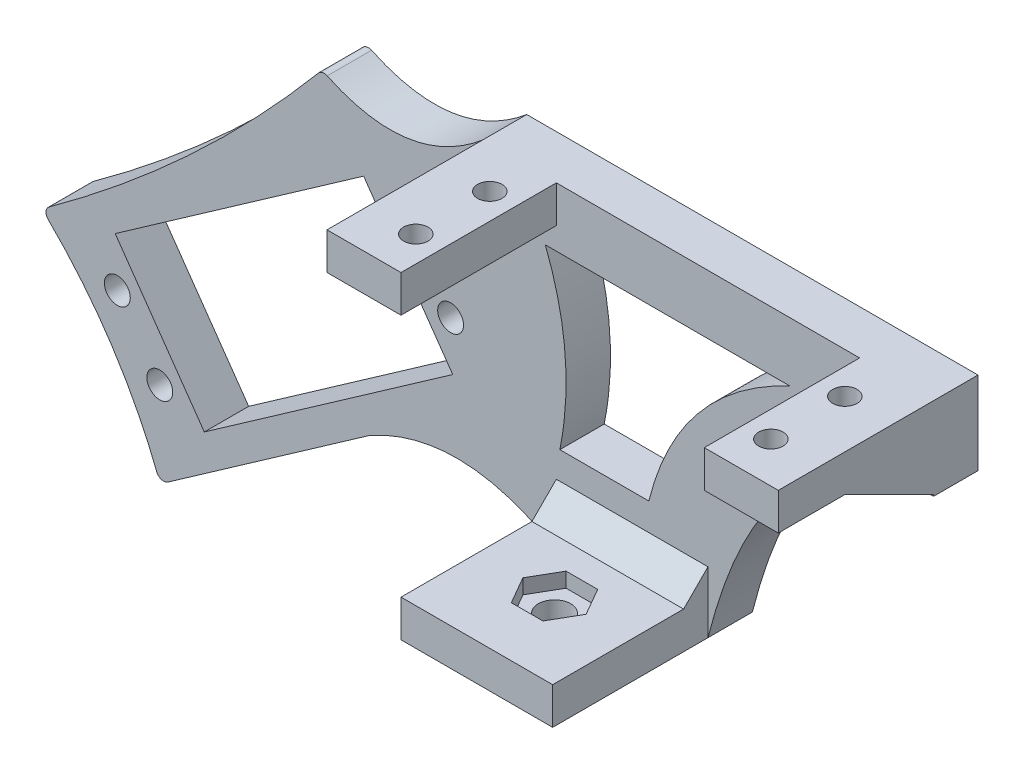
SolidWorks part; units mm, degrees
ref_plane "Front Plane" through (0, 0, 0) normal (0, 0, 1) x (1, 0, 0)
ref_plane "Top Plane" through (0, 0, 0) normal (0, 1, 0) x (1, 0, 0)
ref_plane "Right Plane" through (0, 0, 0) normal (1, 0, 0) x (0, 0, -1)
sketch "Sketch1" plane through (0, 0, 0) normal (0, 0, 1) x (1, 0, 0)
  line L5 (-36.2967, 22.2901) -> (-26.2967, 22.2901)
  line L6 (-36.2967, 22.2901) -> (-36.2967, 17.2901)
  line L7 (-36.2967, 17.2901) -> (-26.2967, 17.2901)
  line L8 (-26.2967, 22.2901) -> (-26.2967, 17.2901)
  line L9 (-36.2967, 22.2901) -> (-26.2967, 17.2901) construction
  line L10 (-36.2967, 17.2901) -> (-26.2967, 22.2901) construction
  line L11 (14.7033, 22.2901) -> (24.7033, 22.2901)
  line L12 (14.7033, 22.2901) -> (14.7033, 17.2901)
  line L13 (14.7033, 17.2901) -> (24.7033, 17.2901)
  line L14 (24.7033, 22.2901) -> (24.7033, 17.2901)
  line L15 (14.7033, 22.2901) -> (24.7033, 17.2901) construction
  line L16 (14.7033, 17.2901) -> (24.7033, 22.2901) construction
  point P0 (-31.2967, 19.7901)
  point P6 (19.7033, 19.7901)
  dimension "D1" = 5
  dimension "D2" = 5
  dimension "D3" = 10
  dimension "D4" = 10
  dimension "D5" = 41
extrude "Boss-Extrude1" add sketch "Sketch1" along normal blind 21
sketch "Sketch2" plane through (0, 0, 21) normal (0, 0, 1) x (1, 0, 0)
  line L0 (-36.2967, 22.2901) -> (24.7033, 22.2901)
  line L1 (24.7033, 22.2901) -> (24.7033, 7.2901)
  line L2 (24.7033, 7.2901) -> (12.7033, 7.2901)
  line L3 (12.7033, 7.2901) -> (-5.7967, -11.2099)
  line L4 (-5.7967, -11.2099) -> (-5.7967, -20.7099)
  line L5 (-5.7967, -20.7099) -> (-36.2967, -20.7099)
  line L6 (-36.2967, -20.7099) -> (-36.2967, 22.2901)
  line L7 (-36.2967, 17.2901) -> (-26.2967, 17.2901) construction
  line L8 (-16.0467, 22.2901) -> (-16.0467, 2.0298) construction
  line L9 (-26.2967, 17.2901) -> (-26.2967, 22.2901) construction
  line L10 (3.5612, 12.2901) -> (-15.7967, -7.0678)
  line L11 (-15.7967, -7.0678) -> (-15.7967, -10.7099)
  line L12 (-15.7967, -10.7099) -> (-26.2967, -10.7099)
  line L13 (-26.2967, -10.7099) -> (-26.2967, 12.2901)
  line L14 (-26.2967, 12.2901) -> (3.5612, 12.2901)
  line L15 (3.5612, 12.2901) -> (3.5612, 12.2901)
  line L16 (3.5612, 12.2901) -> (3.5612, 12.2901)
  dimension "D1" = 38
  dimension "D2" = 15
  dimension "D3" = 10.25
  dimension "D4" = 10.25
  dimension "D5" = 135
  dimension "D6" = 12
  dimension "D7" = 10
extrude "Boss-Extrude2" add sketch "Sketch2" along normal blind 6 contours L6 L0 L1 L2 L3 L4 L5
sketch "Sketch3" plane through (0, 0, 21) normal (0, 0, -1) x (-1, 0, 0)
  line L1 (5.7967, -20.7099) -> (26.2967, -20.7099)
  line L2 (5.7967, -20.7099) -> (5.7967, -15.7099)
  line L3 (5.7967, -15.7099) -> (26.2967, -15.7099)
  line L4 (26.2967, -20.7099) -> (26.2967, -15.7099)
  line L5 (16.0467, 22.2901) -> (16.0467, 17.3696) construction
  line L6 (-14.7033, 22.2901) -> (26.2967, 22.2901) construction
  line L7 (26.2967, 17.2901) -> (26.2967, 22.2901) construction
  line L9 (26.2967, 17.2901) -> (26.2967, 22.2901) construction
  dimension "D1" = 5
  dimension "D2" = 10.25
extrude "Boss-Extrude3" add sketch "Sketch3" along normal blind 21
sketch "Sketch4" plane through (0, 22.2901, 0) normal (0, 1, 0) x (1, 0, 0)
  line L0 (-26.2967, 0) -> (-26.2967, -21) construction
  line L1 (-26.2967, -10.5) -> (-23.5726, -10.5) construction
  line L2 (-26.2967, -21) -> (-26.2967, 0) construction
  circle A0 centre (-29.7967, -5.5) radius 1.65
  circle A1 centre (18.2033, -5.5) radius 1.65
  circle A2 centre (18.2033, -15.5) radius 1.65
  circle A3 centre (-29.7967, -15.5) radius 1.65
  dimension "D1" = 3.3
  dimension "D2" = 3.5
  dimension "D3" = 5
  dimension "D4" = 2
  dimension "D5" = 2
extrude "Cut-Extrude1" cut sketch "Sketch4" against normal up to next
sketch "Sketch5" plane through (0, -15.7099, 0) normal (0, 1, 0) x (1, 0, 0)
  line L0 (-26.2967, 0) -> (-5.7967, 0) construction
  line L1 (-5.7967, 0) -> (-5.7967, -21) construction
  circle A0 centre (-16.0467, -10.5) radius 2.2
  dimension "D1" = 4.4
  dimension "D3" = 10.25
  dimension "D2" = 10.5
extrude "Cut-Extrude2" cut sketch "Sketch5" against normal up to next
sketch "Sketch6" plane through (0, 0, 27) normal (0, 0, 1) x (1, 0, 0)
  line L0 (-36.2967, 22.2901) -> (-36.2967, -20.7099) construction
  line L1 (-85.9329, -13.4688) -> (-52.3477, 10.0479)
  line L2 (-85.9329, -13.4688) -> (-73.8878, -30.671)
  line L3 (-73.8878, -30.671) -> (-40.3026, -7.1543)
  line L4 (-52.3477, 10.0479) -> (-40.3026, -7.1543)
  line L5 (-85.9329, -13.4688) -> (-40.3026, -7.1543) construction
  line L6 (-73.8878, -30.671) -> (-52.3477, 10.0479) construction
  line L7 (-79.8591, -39.7352) -> (-51.5037, -19.8806)
  line L8 (-71.9651, -45.841) -> (-23.4502, -45.841) construction
  line L9 (-79.9104, -22.0699) -> (-76.182, -19.4593) construction
  line L10 (-36.2967, 22.2901) -> (-36.2967, -20.7099)
  line L11 (-36.2967, -20.7099) -> (-5.7967, -20.7099) construction
  circle A0 centre (-85.6453, -19.9816) radius 1.75
  circle A1 centre (-79.9095, -28.1732) radius 1.75
  circle A2 centre (-46.326, 7.55) radius 1.75
  circle A3 centre (-40.5902, -0.6415) radius 1.75
  spline S0 degree 2 poles (-95.8421, -15.5242) (-74.6637, -0.3481) (-57.9628, 19.6612) knots 0 0 0 1 1 1
  spline S1 degree 2 poles (-57.9628, 19.6612) (-46.4471, 13.8149) (-36.2967, 22.2901) knots 0 0 0 1 1 1
  spline S2 degree 2 poles (-95.8421, -15.5242) (-85.0867, -25.7546) (-79.8591, -39.7352) knots 0 0 0 1 1 1
  spline S3 degree 2 poles (-51.5037, -19.8806) (-43.7779, -18.4911) (-36.2967, -20.7099) knots 0 0 0 1 1 1
  point P0 (-63.1177, -10.3116)
  line M9 (-36.2967, 22.2901) -> (-36.2967, -20.7099)
  dimension "D5" = 3.5
  dimension "D8" = 3.5
  dimension "D9" = 3.5
  dimension "D10" = 3.5
  dimension "D1" = 41
  dimension "D2" = 21
  dimension "D3" = 8
  dimension "D4" = 35
  dimension "D6" = 3.5
  dimension "D7" = 5
  dimension "D11" = 3.5
  dimension "D12" = 10
  dimension "D13" = 10
  dimension "D14" = 3.5
  dimension "D15" = 3.5
  dimension "D16" = 5
  dimension "D17" = 4
  dimension "D18" = 4
extrude "Boss-Extrude4" add sketch "Sketch6" against normal up to surface (6 mm away) contours L7 S3 A3 S1 S0 S2 L1 L4 L3 L2 A0 A1 A2 M9 up to face at (-7.5275, 3.4055, 21)
sketch "Sketch7" plane through (0, 0, 21) normal (0, 0, -1) x (-1, 0, 0)
  line L0 (36.2967, -20.7099) -> (26.2967, -20.7099) construction
  line L1 (36.2967, -20.7099) -> (26.2967, -20.7099)
  parabola Q0 (51.5037, -19.8806) -> (36.2967, -20.7099) focus (44.501, -35.4126) apex (43.4171, -19.419) construction
  parabola Q1 (51.5037, -19.8806) -> (36.2967, -20.7099) focus (44.501, -35.4126) apex (43.4171, -19.419)
  spline S0 degree 2 poles (26.2967, -20.7099) (39.1597, -13.0568) (51.5037, -19.8806) knots 0 0 0 1 1 1
extrude "Cut-Extrude3" cut sketch "Sketch7" against normal up to next
sketch "Sketch10" plane through (0, 0, 27) normal (0, 0, 1) x (1, 0, 0)
  line L0 (5.2668, 14.2901) -> (-27.7882, 14.2901)
  line L1 (-36.2967, 22.2901) -> (24.7033, 22.2901) construction
  line L2 (-25.8237, -8.7099) -> (-13.7967, -8.7099)
  line L3 (-5.7967, -11.2099) -> (-5.7967, -20.7099) construction
  line L4 (-5.7967, -20.7099) -> (-26.2967, -20.7099) construction
  spline S2 degree 2 poles (5.2668, 14.2901) (-9.8422, 7.1853) (-13.7967, -8.7099) knots 0 0 0 1 1 1
  spline S3 degree 2 poles (-27.7882, 14.2901) (-23.4314, 3.1329) (-25.8237, -8.7099) knots 0 0 0 1 1 1
  dimension "D1" = 8
  dimension "D2" = 8
  dimension "D3" = 12
extrude "Cut-Extrude7" cut sketch "Sketch10" against normal up to next
sketch "Sketch11" plane through (0, 0, 27) normal (0, 0, 1) x (1, 0, 0)
  line L1 (24.7033, 7.2901) -> (12.7033, 7.2901) construction
  line L2 (12.7033, 7.2901) -> (-5.7967, -11.2099) construction
  line L3 (-5.7967, -11.2099) -> (-5.7967, -20.7099) construction
  line L4 (15.1192, 7.2901) -> (12.7033, 7.2901)
  line L5 (12.7033, 7.2901) -> (-5.7967, -11.2099)
  line L6 (-5.7967, -11.2099) -> (-5.7967, -20.7099)
  spline S0 degree 2 poles (-5.7967, -20.7099) (-0.0669, -3.0227) (15.1192, 7.2901) knots 0 0 0 1 1 1
extrude "Boss-Extrude5" add sketch "Sketch11" against normal up to surface (6 mm away) up to face at (-18.1639, 2.7901, 21)
sketch "Sketch12" plane through (24.7033, 0, 0) normal (1, 0, 0) x (0, 0, -1)
  line L0 (-21, 11.2901) -> (-9, 17.2901)
  line L1 (-21, 17.2901) -> (-21, 7.2901) construction
  line L2 (-21, 17.2901) -> (0, 17.2901) construction
  line L3 (-9, 17.2901) -> (-21, 17.2901)
  line L4 (-21, 17.2901) -> (-21, 11.2901)
  dimension "D1" = 6
  dimension "D2" = 12
extrude "Boss-Extrude6" add sketch "Sketch12" against normal blind 3
sketch "Sketch13" plane through (-36.2967, 0, 0) normal (-1, 0, 0) x (0, 0, 1)
  line L3 (21, 11.2901) -> (21, 17.2901)
  line L4 (21, 17.2901) -> (9, 17.2901)
  line L5 (9, 17.2901) -> (21, 11.2901)
  line L6 (21, 11.2901) -> (21, 17.2901)
  line L7 (21, 17.2901) -> (9, 17.2901)
  line L8 (9, 17.2901) -> (21, 11.2901)
  dimension "D1" = 0
extrude "Boss-Extrude7" add sketch "Sketch13" against normal blind 3
sketch "Sketch14" plane through (-5.7967, 0, 0) normal (1, 0, 0) x (0, 0, -1)
  line L0 (-17.7, -15.7099) -> (-21, -12.4099)
  line L1 (0, -15.7099) -> (-21, -15.7099) construction
  line L2 (-21, -20.7099) -> (-21, 7.2901) construction
  line L3 (-21, -12.4099) -> (-21, -15.7099)
  line L4 (-21, -15.7099) -> (-17.7, -15.7099)
  dimension "D1" = 3.3
  dimension "D2" = 3.3
extrude "Boss-Extrude8" add sketch "Sketch14" against normal up to surface (20.5 mm away) up to face at (-26.2967, -18.2099, 10.5)
ref_plane "Plane1" through (0, 0, 24) normal (0, 0, -1) x (-1, 0, 0)
mirror "Mirror1" about plane through (0, 0, 24) normal (0, 0, -1) of "Cut-Extrude2", "Boss-Extrude1", "Cut-Extrude1", "Boss-Extrude6", "Boss-Extrude7", "Boss-Extrude8", "Boss-Extrude3"
sketch "Sketch16" plane through (0, 0, 0) normal (0, 0, -1) x (-1, 0, 0)
  line L1 (-24.7033, 22.2901) -> (36.7204, 22.2901)
  line L2 (-24.7033, 22.2901) -> (-24.7033, -23.0622)
  line L3 (-24.7033, -23.0622) -> (36.7204, -23.0622)
  line L4 (36.7204, 22.2901) -> (36.7204, -23.0622)
extrude "Cut-Extrude8" cut sketch "Sketch16" against normal up to surface (21 mm away) up to face at (-18.1639, 2.7901, 21)
sketch "Sketch17" plane through (0, 0, 21) normal (0, 0, -1) x (-1, 0, 0)
  line L0 (-24.7033, 7.2901) -> (-24.7033, 11.0901)
  line L1 (-24.7033, 22.2901) -> (-24.7033, 7.2901) construction
  line L2 (-24.7033, 7.2901) -> (-15.1192, 7.2901) construction
  line L3 (-24.7033, 7.2901) -> (-15.1192, 7.2901)
  parabola Q0 (5.7967, -20.7099) -> (-15.1192, 7.2901) focus (-23.0101, -19.6791) apex (-2.9383, -4.0263) construction
  parabola Q1 (5.7967, -20.7099) -> (-15.1192, 7.2901) focus (-23.0101, -19.6791) apex (-2.9383, -4.0263)
  spline S0 degree 2 poles (5.7967, -20.7099) (-1.8909, 9.8453) (-24.7033, 11.0901) knots 0 0 0 1 1 1
  dimension "D1" = 3.8
  dimension "D2" = 3.5
  dimension "D3" = 3
extrude "Cut-Extrude9" cut sketch "Sketch17" against normal up to surface (6 mm away) up to face at (-18.1639, 2.7901, 27)
fillet "Fillet1" radius 1 3 edges at (-79.8591, -39.7352, 24) (-95.8421, -15.5242, 24) (-57.9628, 19.6612, 24)
sketch "Sketch18" plane through (0, -15.7099, 0) normal (0, 1, 0) x (1, 0, 0)
  line L0 (-26.2967, -30.3) -> (-5.7967, -30.3) construction
  line L1 (-18.1829, -41.2) -> (-13.9105, -41.2)
  line L2 (-13.9105, -41.2) -> (-11.7743, -37.5)
  line L3 (-11.7743, -37.5) -> (-13.9105, -33.8)
  line L4 (-13.9105, -33.8) -> (-18.1829, -33.8)
  line L5 (-18.1829, -33.8) -> (-20.3191, -37.5)
  line L6 (-20.3191, -37.5) -> (-18.1829, -41.2)
  circle A0 centre (-16.0467, -37.5) radius 3.7 construction
  dimension "D1" = 7.4
extrude "Cut-Extrude10" cut sketch "Sketch18" against normal blind 2
